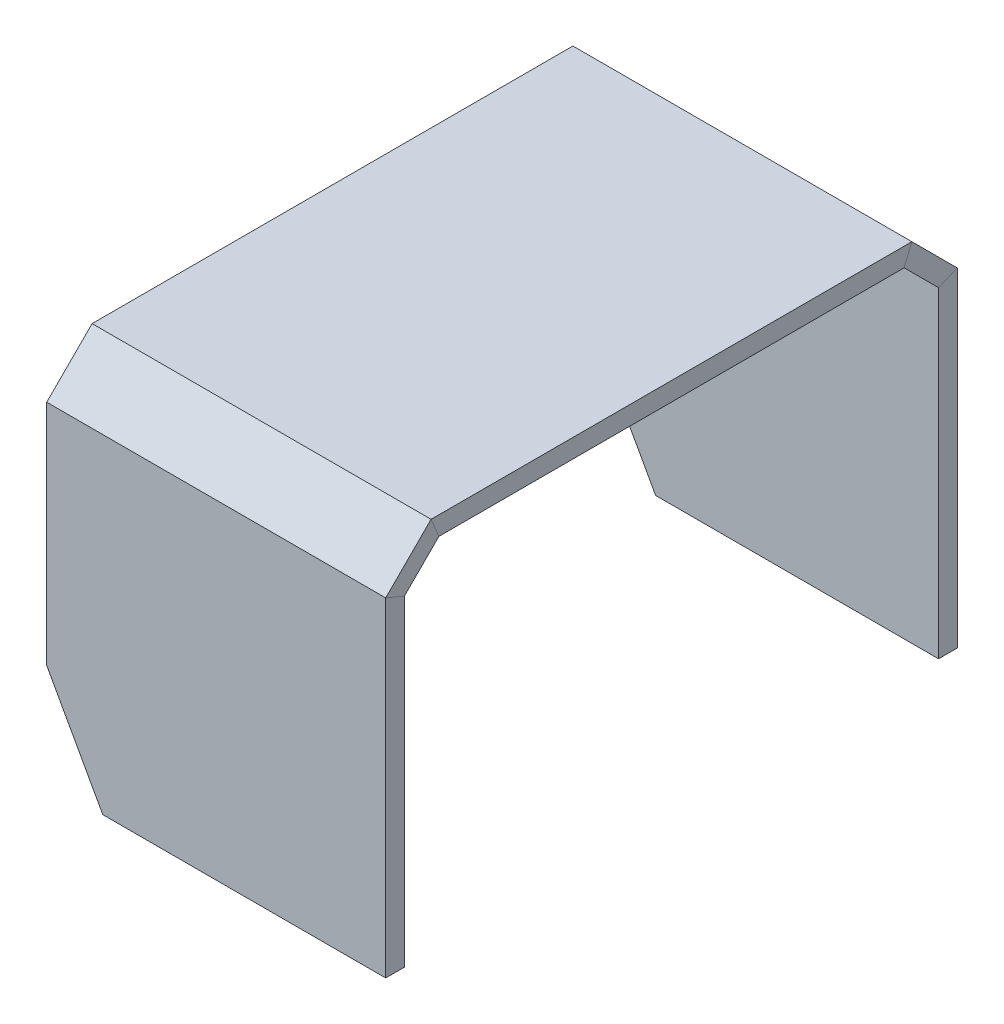
SolidWorks part; units mm, degrees
other "Markup1"
sketch "Sketch7" plane through (30.439, 0, -76.3) normal (1, 0, 0) x (0, 0, -1)
ref_plane "Front Plane" through (0, 0, 0) normal (0, 0, 1) x (1, 0, 0)
ref_plane "Top Plane" through (0, 0, 0) normal (0, 1, 0) x (1, 0, 0)
ref_plane "Right Plane" through (0, 0, 0) normal (1, 0, 0) x (0, 0, -1)
sketch "Sketch1" plane through (0, 0, 0) normal (0, 1, 0) x (1, 0, 0)
  line L1 (-50, -71.3) -> (23.5, -71.3)
  line L2 (-50, -71.3) -> (-50, -76.3)
  line L3 (-50, -76.3) -> (23.5, -76.3)
  line L4 (23.5, -71.3) -> (23.5, -76.3)
  line L5 (-50, -71.3) -> (23.5, -76.3) construction
  line L6 (-50, -76.3) -> (23.5, -71.3) construction
  line L7 (-50, 76.3) -> (23.5, 76.3) construction
  line L8 (-50, 76.3) -> (-50, 71.3) construction
  line L9 (-50, 71.3) -> (23.5, 71.3) construction
  line L10 (23.5, 76.3) -> (23.5, 71.3) construction
  line L11 (-50, 76.3) -> (23.5, 71.3) construction
  line L12 (-50, 71.3) -> (23.5, 76.3) construction
  point P4 (-13.25, -73.8)
  point P9 (-13.25, 73.8)
  dimension "D1" = 152.6
  dimension "D2" = 5
  dimension "D3" = 5
  dimension "D4" = 73.5
  dimension "D5" = 73.5
  dimension "D6" = 76.3
  dimension "D7" = 50
  dimension "D8" = 50
sketch "Sketch2" plane through (0, 0, 0) normal (1, 0, 0) x (0, 0, -1)
  line L0 (-73.8, 0) -> (-73.8, 86.85)
  line L1 (73.8, 0) -> (73.8, 86.85)
  line L2 (76.3, 0) -> (71.3, 0) construction
  line L3 (63.15, 97.5) -> (-63.15, 97.5)
  line L4 (-73.8, 86.85) -> (-63.15, 97.5)
  line L5 (63.15, 97.5) -> (73.8, 86.85)
  point P1 (0, 97.5)
  dimension "D2" = 0
  dimension "D3" = 97.5
  dimension "D4" = 0
sweep "Sweep3" add profiles "Sketch1" path "Sketch2"
ref_plane "Plane1" through (20, 0, 0) normal (1, 0, 0) x (0, 0, -1)
sketch "Sketch3" plane through (20, 0, 0) normal (1, 0, 0) x (0, 0, -1)
  line L1 (-76.3, 87.8855) -> (-64.1855, 100)
  line L2 (-64.1855, 100) -> (64.1855, 100)
  line L3 (64.1855, 100) -> (76.3, 87.8855)
  line L7 (71.3, 85.8145) -> (62.1145, 95)
  line L8 (62.1145, 95) -> (-62.1145, 95)
  line L9 (-62.1145, 95) -> (-71.3, 85.8145)
  line L12 (-76.3, 87.8855) -> (-71.3, 85.8145)
  line L13 (71.3, 85.8145) -> (76.3, 87.8855)
sketch "Sketch4" plane through (0, 100, 0) normal (0, 1, 0) x (1, 0, 0)
  point P0 (30.439, 28.6485)
sketch "Sketch5" plane through (-50, 0, 0) normal (-1, 0, 0) x (0, 0, 1)
  line L0 (-76.3, 0) -> (-71.3, 0)
  line L1 (-71.3, 0) -> (-71.3, 85.8145)
  line L2 (-71.3, 85.8145) -> (-62.1145, 95)
  line L3 (-62.1145, 95) -> (62.1145, 95)
  line L4 (62.1145, 95) -> (71.3, 85.8145)
  line L5 (71.3, 85.8145) -> (71.3, 0)
  line L6 (71.3, 0) -> (76.3, 0)
  line L7 (76.3, 0) -> (76.3, 87.8855)
  line L8 (76.3, 87.8855) -> (64.1855, 100)
  line L9 (64.1855, 100) -> (-64.1855, 100)
  line L10 (-64.1855, 100) -> (-76.3, 87.8855)
  line L11 (-76.3, 87.8855) -> (-76.3, 0)
extrude "Boss-Extrude1" add sketch "Sketch5" along normal blind 17
sketch "Sketch6" plane through (0, 0, -76.3) normal (0, 0, -1) x (-1, 0, 0)
  line L6 (52.03, 0) -> (67, 27)
  line L7 (67, 0) -> (-23.5, 0) construction
  line L8 (67, 87.8855) -> (67, 0) construction
  line L9 (67, 27) -> (67, 0)
  line L10 (67, 0) -> (52.03, 0)
  dimension "D1" = 14.97
  dimension "D2" = 27
extrude "Cut-Extrude1" cut sketch "Sketch6" against normal through all
sketch "Sketch8" plane through (20, 0, 0) normal (1, 0, 0) x (0, 0, -1)
  line L0 (-76.3, 87.8855) -> (-71.3, 85.8145)
  line L1 (-71.3, 85.8145) -> (-62.1145, 95)
  line L2 (-62.1145, 95) -> (62.1145, 95)
  line L3 (62.1145, 95) -> (71.3, 85.8145)
  line L4 (71.3, 85.8145) -> (76.3, 87.8855)
  line L5 (76.3, 87.8855) -> (64.1855, 100)
  line L6 (64.1855, 100) -> (-64.1855, 100)
  line L7 (-64.1855, 100) -> (-76.3, 87.8855)
